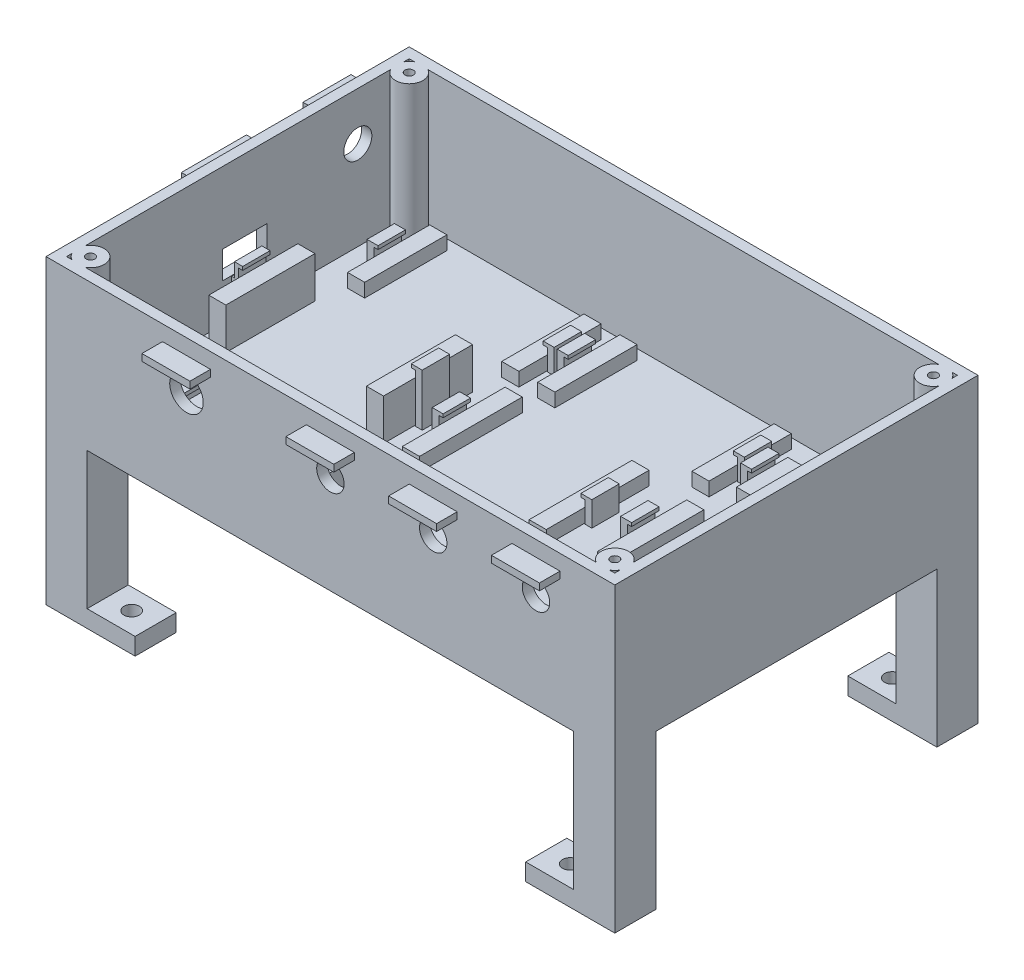
SolidWorks part; units mm, degrees
material "PETG"
ref_plane "Front Plane" through (0, 0, 0) normal (0, 0, 1) x (1, 0, 0)
ref_plane "Top Plane" through (0, 0, 0) normal (0, 1, 0) x (1, 0, 0)
ref_plane "Right Plane" through (0, 0, 0) normal (1, 0, 0) x (0, 0, -1)
other "Configuration Table"
sketch "Sketch1" plane through (0, 0, 0) normal (0, 1, 0) x (1, 0, 0)
  line L0 (-83, -53) -> (83, -53)
  line L1 (83, -53) -> (83, 53)
  line L2 (83, 53) -> (-83, 53)
  line L3 (-83, 53) -> (-83, -53)
extrude "Box_Shell" add sketch "Sketch1" along normal blind 43 from offset 45
sketch "Sketch2" plane through (0, 0, 0) normal (0, 1, 0) x (1, 0, 0)
  line L1 (-80, -50) -> (80, -50)
  line L2 (-80, -50) -> (-80, 50)
  line L3 (-80, 50) -> (80, 50)
  line L4 (80, -50) -> (80, 50)
  line L5 (-80, -50) -> (80, 50) construction
  line L6 (-80, 50) -> (80, -50) construction
  point P6 (0, 0)
  dimension "D1" = 160
  dimension "D2" = 100
extrude "Box_Cavity" cut sketch "Sketch2" against normal blind 40 from offset 88
sketch "Sketch3" plane through (0, 0, 0) normal (0, 1, 0) x (1, 0, 0)
  circle A0 centre (-76.5, 46.5) radius 4
  circle A1 centre (-76.5, -46.5) radius 4
  circle A2 centre (76.5, 46.5) radius 4
  circle A3 centre (76.5, -46.5) radius 4
  dimension "D1" = 8
  dimension "D2" = 8
  dimension "D3" = 8
  dimension "D4" = 8
extrude "Lid_Bosses" add sketch "Sketch3" along normal blind 40 from offset 48
sketch "Sketch4" plane through (0, 0, 0) normal (0, 1, 0) x (1, 0, 0)
  circle A0 centre (-76.5, 46.5) radius 1.25
  circle A1 centre (-76.5, -46.5) radius 1.25
  circle A2 centre (76.5, 46.5) radius 1.25
  circle A3 centre (76.5, -46.5) radius 1.25
  dimension "D1" = 2.5
  dimension "D2" = 2.5
  dimension "D3" = 2.5
  dimension "D4" = 2.5
extrude "Lid_Screw_Holes_M3" cut sketch "Sketch4" against normal blind 12 from offset 88
sketch "Sketch5" plane through (0, 0, 0) normal (0, 1, 0) x (1, 0, 0)
  line L0 (-83, 41) -> (-71, 41)
  line L1 (-71, 41) -> (-71, 53)
  line L2 (-71, 53) -> (-83, 53)
  line L3 (-83, 53) -> (-83, 41)
  line L4 (-83, -53) -> (-71, -53)
  line L5 (-71, -53) -> (-71, -41)
  line L6 (-71, -41) -> (-83, -41)
  line L7 (-83, -41) -> (-83, -53)
  line L8 (71, 41) -> (83, 41)
  line L9 (83, 41) -> (83, 53)
  line L10 (83, 53) -> (71, 53)
  line L11 (71, 53) -> (71, 41)
  line L12 (71, -53) -> (83, -53)
  line L13 (83, -53) -> (83, -41)
  line L14 (83, -41) -> (71, -41)
  line L15 (71, -41) -> (71, -53)
extrude "Legs" add sketch "Sketch5" along normal blind 45
sketch "Sketch6" plane through (0, 0, 0) normal (0, 1, 0) x (1, 0, 0)
  line L0 (-83, 41) -> (-57, 41)
  line L1 (-57, 41) -> (-57, 53)
  line L2 (-57, 53) -> (-83, 53)
  line L3 (-83, 53) -> (-83, 41)
  line L4 (-83, -53) -> (-57, -53)
  line L5 (-57, -53) -> (-57, -41)
  line L6 (-57, -41) -> (-83, -41)
  line L7 (-83, -41) -> (-83, -53)
  line L8 (57, 41) -> (83, 41)
  line L9 (83, 41) -> (83, 53)
  line L10 (83, 53) -> (57, 53)
  line L11 (57, 53) -> (57, 41)
  line L12 (57, -53) -> (83, -53)
  line L13 (83, -53) -> (83, -41)
  line L14 (83, -41) -> (57, -41)
  line L15 (57, -41) -> (57, -53)
extrude "Leg_Pads" add sketch "Sketch6" along normal blind 5
sketch "Sketch7" plane through (0, 0, 0) normal (0, 1, 0) x (1, 0, 0)
  circle A0 centre (-64, 47) radius 2.25
  circle A1 centre (-64, -47) radius 2.25
  circle A2 centre (64, 47) radius 2.25
  circle A3 centre (64, -47) radius 2.25
  dimension "D1" = 4.5
  dimension "D2" = 4.5
  dimension "D3" = 4.5
  dimension "D4" = 4.5
extrude "Leg_Holes_M4" cut sketch "Sketch7" along normal blind 6 from offset 0.5
sketch "Sketch8" plane through (0, 0, 0) normal (0, 1, 0) x (1, 0, 0)
  line L0 (-19, -13) -> (-14, -13)
  line L1 (-14, -13) -> (-14, 17)
  line L2 (-14, 17) -> (-19, 17)
  line L3 (-19, 17) -> (-19, -13)
  line L4 (18, -13) -> (23, -13)
  line L5 (23, -13) -> (23, 17)
  line L6 (23, 17) -> (18, 17)
  line L7 (18, 17) -> (18, -13)
  line L8 (36, -11) -> (41, -11)
  line L9 (41, -11) -> (41, 15)
  line L10 (41, 15) -> (36, 15)
  line L11 (36, 15) -> (36, -11)
  line L12 (69, -11) -> (74, -11)
  line L13 (74, -11) -> (74, 15)
  line L14 (74, 15) -> (69, 15)
  line L15 (69, 15) -> (69, -11)
  line L16 (-71, 23) -> (-66, 23)
  line L17 (-66, 23) -> (-66, 47)
  line L18 (-66, 47) -> (-71, 47)
  line L19 (-71, 47) -> (-71, 23)
  line L20 (-26, 23) -> (-21, 23)
  line L21 (-21, 23) -> (-21, 47)
  line L22 (-21, 47) -> (-26, 47)
  line L23 (-26, 47) -> (-26, 23)
  line L24 (-15.5, 23) -> (-10.5, 23)
  line L25 (-10.5, 23) -> (-10.5, 47)
  line L26 (-10.5, 47) -> (-15.5, 47)
  line L27 (-15.5, 47) -> (-15.5, 23)
  line L28 (29.5, 23) -> (34.5, 23)
  line L29 (34.5, 23) -> (34.5, 47)
  line L30 (34.5, 47) -> (29.5, 47)
  line L31 (29.5, 47) -> (29.5, 23)
  line L32 (40, 25.5) -> (45, 25.5)
  line L33 (45, 25.5) -> (45, 40.5)
  line L34 (45, 40.5) -> (40, 40.5)
  line L35 (40, 40.5) -> (40, 25.5)
  line L36 (69, 25.5) -> (74, 25.5)
  line L37 (74, 25.5) -> (74, 40.5)
  line L38 (74, 40.5) -> (69, 40.5)
  line L39 (69, 40.5) -> (69, 25.5)
  line L40 (-62, -46) -> (-57, -46)
  line L41 (-57, -46) -> (-57, -18)
  line L42 (-57, -18) -> (-62, -18)
  line L43 (-62, -18) -> (-62, -46)
  line L44 (-27, -46) -> (-22, -46)
  line L45 (-22, -46) -> (-22, -18)
  line L46 (-22, -18) -> (-27, -18)
  line L47 (-27, -18) -> (-27, -46)
extrude "Board_Pads_4mm" add sketch "Sketch8" along normal blind 4 from offset 48
sketch "Sketch9" plane through (0, 0, 0) normal (0, 1, 0) x (1, 0, 0)
  line L0 (-21.3, -2) -> (-19.3, -2)
  line L1 (-19.3, -2) -> (-19.3, 6)
  line L2 (-19.3, 6) -> (-21.3, 6)
  line L3 (-21.3, 6) -> (-21.3, -2)
  line L4 (23.3, -2) -> (25.3, -2)
  line L5 (25.3, -2) -> (25.3, 6)
  line L6 (25.3, 6) -> (23.3, 6)
  line L7 (23.3, 6) -> (23.3, -2)
  line L8 (33.7, -2) -> (35.7, -2)
  line L9 (35.7, -2) -> (35.7, 6)
  line L10 (35.7, 6) -> (33.7, 6)
  line L11 (33.7, 6) -> (33.7, -2)
  line L12 (74.3, -2) -> (76.3, -2)
  line L13 (76.3, -2) -> (76.3, 6)
  line L14 (76.3, 6) -> (74.3, 6)
  line L15 (74.3, 6) -> (74.3, -2)
  line L16 (-73.3, 31) -> (-71.3, 31)
  line L17 (-71.3, 31) -> (-71.3, 39)
  line L18 (-71.3, 39) -> (-73.3, 39)
  line L19 (-73.3, 39) -> (-73.3, 31)
  line L20 (-20.7, 31) -> (-18.7, 31)
  line L21 (-18.7, 31) -> (-18.7, 39)
  line L22 (-18.7, 39) -> (-20.7, 39)
  line L23 (-20.7, 39) -> (-20.7, 31)
  line L24 (-17.8, 31) -> (-15.8, 31)
  line L25 (-15.8, 31) -> (-15.8, 39)
  line L26 (-15.8, 39) -> (-17.8, 39)
  line L27 (-17.8, 39) -> (-17.8, 31)
  line L28 (34.8, 31) -> (36.8, 31)
  line L29 (36.8, 31) -> (36.8, 39)
  line L30 (36.8, 39) -> (34.8, 39)
  line L31 (34.8, 39) -> (34.8, 31)
  line L32 (37.7, 29) -> (39.7, 29)
  line L33 (39.7, 29) -> (39.7, 37)
  line L34 (39.7, 37) -> (37.7, 37)
  line L35 (37.7, 37) -> (37.7, 29)
  line L36 (74.3, 29) -> (76.3, 29)
  line L37 (76.3, 29) -> (76.3, 37)
  line L38 (76.3, 37) -> (74.3, 37)
  line L39 (74.3, 37) -> (74.3, 29)
  line L40 (-64.3, -36) -> (-62.3, -36)
  line L41 (-62.3, -36) -> (-62.3, -28)
  line L42 (-62.3, -28) -> (-64.3, -28)
  line L43 (-64.3, -28) -> (-64.3, -36)
  line L44 (-21.7, -36) -> (-19.7, -36)
  line L45 (-19.7, -36) -> (-19.7, -28)
  line L46 (-19.7, -28) -> (-21.7, -28)
  line L47 (-21.7, -28) -> (-21.7, -36)
extrude "Board_Clips_4mm" add sketch "Sketch9" along normal blind 7.2 from offset 48
sketch "Sketch10" plane through (0, 0, 0) normal (0, 1, 0) x (1, 0, 0)
  line L0 (-19.3, -2) -> (-18.1, -2)
  line L1 (-18.1, -2) -> (-18.1, 6)
  line L2 (-18.1, 6) -> (-19.3, 6)
  line L3 (-19.3, 6) -> (-19.3, -2)
  line L4 (22.1, -2) -> (23.3, -2)
  line L5 (23.3, -2) -> (23.3, 6)
  line L6 (23.3, 6) -> (22.1, 6)
  line L7 (22.1, 6) -> (22.1, -2)
  line L8 (35.7, -2) -> (36.9, -2)
  line L9 (36.9, -2) -> (36.9, 6)
  line L10 (36.9, 6) -> (35.7, 6)
  line L11 (35.7, 6) -> (35.7, -2)
  line L12 (73.1, -2) -> (74.3, -2)
  line L13 (74.3, -2) -> (74.3, 6)
  line L14 (74.3, 6) -> (73.1, 6)
  line L15 (73.1, 6) -> (73.1, -2)
  line L16 (-71.3, 31) -> (-70.1, 31)
  line L17 (-70.1, 31) -> (-70.1, 39)
  line L18 (-70.1, 39) -> (-71.3, 39)
  line L19 (-71.3, 39) -> (-71.3, 31)
  line L20 (-21.9, 31) -> (-20.7, 31)
  line L21 (-20.7, 31) -> (-20.7, 39)
  line L22 (-20.7, 39) -> (-21.9, 39)
  line L23 (-21.9, 39) -> (-21.9, 31)
  line L24 (-15.8, 31) -> (-14.6, 31)
  line L25 (-14.6, 31) -> (-14.6, 39)
  line L26 (-14.6, 39) -> (-15.8, 39)
  line L27 (-15.8, 39) -> (-15.8, 31)
  line L28 (33.6, 31) -> (34.8, 31)
  line L29 (34.8, 31) -> (34.8, 39)
  line L30 (34.8, 39) -> (33.6, 39)
  line L31 (33.6, 39) -> (33.6, 31)
  line L32 (39.7, 29) -> (40.9, 29)
  line L33 (40.9, 29) -> (40.9, 37)
  line L34 (40.9, 37) -> (39.7, 37)
  line L35 (39.7, 37) -> (39.7, 29)
  line L36 (73.1, 29) -> (74.3, 29)
  line L37 (74.3, 29) -> (74.3, 37)
  line L38 (74.3, 37) -> (73.1, 37)
  line L39 (73.1, 37) -> (73.1, 29)
  line L40 (-62.3, -36) -> (-61.1, -36)
  line L41 (-61.1, -36) -> (-61.1, -28)
  line L42 (-61.1, -28) -> (-62.3, -28)
  line L43 (-62.3, -28) -> (-62.3, -36)
  line L44 (-22.9, -36) -> (-21.7, -36)
  line L45 (-21.7, -36) -> (-21.7, -28)
  line L46 (-21.7, -28) -> (-22.9, -28)
  line L47 (-22.9, -28) -> (-22.9, -36)
extrude "Clip_Lips_4mm" add sketch "Sketch10" along normal blind 1 from offset 54.2
sketch "Sketch11" plane through (0, 0, 0) normal (0, 1, 0) x (1, 0, 0)
  line L0 (-77.5, -11) -> (-72.5, -11)
  line L1 (-72.5, -11) -> (-72.5, 15)
  line L2 (-72.5, 15) -> (-77.5, 15)
  line L3 (-77.5, 15) -> (-77.5, -11)
  line L4 (-31.5, -11) -> (-26.5, -11)
  line L5 (-26.5, -11) -> (-26.5, 15)
  line L6 (-26.5, 15) -> (-31.5, 15)
  line L7 (-31.5, 15) -> (-31.5, -11)
extrude "Board_Pads_12mm" add sketch "Sketch11" along normal blind 12 from offset 48
sketch "Sketch12" plane through (0, 0, 0) normal (0, 1, 0) x (1, 0, 0)
  line L0 (-79.8, -2) -> (-77.8, -2)
  line L1 (-77.8, -2) -> (-77.8, 6)
  line L2 (-77.8, 6) -> (-79.8, 6)
  line L3 (-79.8, 6) -> (-79.8, -2)
  line L4 (-26.2, -2) -> (-24.2, -2)
  line L5 (-24.2, -2) -> (-24.2, 6)
  line L6 (-24.2, 6) -> (-26.2, 6)
  line L7 (-26.2, 6) -> (-26.2, -2)
extrude "Board_Clips_12mm" add sketch "Sketch12" along normal blind 15.2 from offset 48
sketch "Sketch13" plane through (0, 0, 0) normal (0, 1, 0) x (1, 0, 0)
  line L0 (-77.8, -2) -> (-76.6, -2)
  line L1 (-76.6, -2) -> (-76.6, 6)
  line L2 (-76.6, 6) -> (-77.8, 6)
  line L3 (-77.8, 6) -> (-77.8, -2)
  line L4 (-27.4, -2) -> (-26.2, -2)
  line L5 (-26.2, -2) -> (-26.2, 6)
  line L6 (-26.2, 6) -> (-27.4, 6)
  line L7 (-27.4, 6) -> (-27.4, -2)
extrude "Clip_Lips_12mm" add sketch "Sketch13" along normal blind 1 from offset 62.2
sketch "Sketch14" plane through (0, 0, 0) normal (0, 0, 1) x (1, 0, 0)
  circle A0 centre (-42, 74) radius 4.9
  circle A1 centre (0, 74) radius 4
  circle A2 centre (30, 74) radius 4
  circle A3 centre (60, 74) radius 4
  dimension "D1" = 9.8
  dimension "D2" = 8
  dimension "D3" = 8
  dimension "D4" = 8
extrude "Front_Wall_Holes" cut sketch "Sketch14" along normal blind 5 from offset 49
sketch "Sketch15" plane through (0, 0, 0) normal (0, 1, 0) x (1, 0, 0)
  line L0 (-49, -59) -> (-35, -59)
  line L1 (-35, -59) -> (-35, -53)
  line L2 (-35, -53) -> (-49, -53)
  line L3 (-49, -53) -> (-49, -59)
  line L4 (-7, -59) -> (7, -59)
  line L5 (7, -59) -> (7, -53)
  line L6 (7, -53) -> (-7, -53)
  line L7 (-7, -53) -> (-7, -59)
  line L8 (23, -59) -> (37, -59)
  line L9 (37, -59) -> (37, -53)
  line L10 (37, -53) -> (23, -53)
  line L11 (23, -53) -> (23, -59)
  line L12 (53, -59) -> (67, -59)
  line L13 (67, -59) -> (67, -53)
  line L14 (67, -53) -> (53, -53)
  line L15 (53, -53) -> (53, -59)
extrude "Front_Drip_Lips" add sketch "Sketch15" along normal blind 2 from offset 81.5
sketch "Sketch16" plane through (0, 0, 0) normal (1, 0, 0) x (0, 0, -1)
  line L1 (-4.5, 59.1) -> (8.5, 59.1)
  line L2 (-4.5, 59.1) -> (-4.5, 67.1)
  line L3 (-4.5, 67.1) -> (8.5, 67.1)
  line L4 (8.5, 59.1) -> (8.5, 67.1)
  line L5 (-4.5, 59.1) -> (8.5, 67.1) construction
  line L6 (-4.5, 67.1) -> (8.5, 59.1) construction
  circle A0 centre (35, 74) radius 4.1
  point P2 (2, 63.1)
  point P7 (2, 63.1)
  dimension "D1" = 8.2
  dimension "D2" = 13
  dimension "D3" = 8
extrude "Left_Wall_Holes" cut sketch "Sketch16" along normal blind 5 from offset 84
sketch "Sketch17" plane through (0, 0, 0) normal (0, 1, 0) x (1, 0, 0)
  line L0 (-89, 28) -> (-83, 28)
  line L1 (-83, 28) -> (-83, 42)
  line L2 (-83, 42) -> (-89, 42)
  line L3 (-89, 42) -> (-89, 28)
  line L4 (-89, -7.5) -> (-83, -7.5)
  line L5 (-83, -7.5) -> (-83, 11.5)
  line L6 (-83, 11.5) -> (-89, 11.5)
  line L7 (-89, 11.5) -> (-89, -7.5)
extrude "Left_Drip_Lips" add sketch "Sketch17" along normal blind 2 from offset 81.5
equation "\"Jar_OD\"= 90  'ASSUMED - Part C fallback - jar outer diameter"
equation "\"Jar_H\"= 120  'ASSUMED - Part C fallback - jar height"
equation "\"Pump_L\"= 45  'ASSUMED - Part C fallback"
equation "\"Pump_W\"= 24  'ASSUMED - Part C fallback"
equation "\"Pump_H\"= 33  'ASSUMED - Part C fallback"
equation "\"Pump_Outlet_OD\"= 7.5  'ASSUMED - Part C fallback"
equation "\"Tube_OD\"= 8  'ASSUMED - Part C fallback"
equation "\"Tube_ID\"= 6  'ASSUMED - Part C fallback"
equation "\"TDS_Body_Dia\"= 12  'ASSUMED - Part C fallback"
equation "\"TDS_Wet_Len\"= 45  'ASSUMED - Part C fallback - length in water"
equation "\"DS_Tube_Dia\"= 6  'ASSUMED - Part C fallback"
equation "\"DS_Tube_Len\"= 50  'ASSUMED - Part C fallback"
equation "\"ORP_Body_Dia\"= 12  'ASSUMED - Part C fallback"
equation "\"ORP_Body_Len\"= 150  'ASSUMED - Part C fallback"
equation "\"ORP_Cap_Dia\"= 16  'ASSUMED - Part C fallback"
equation "\"Turb_W\"= 33  'ASSUMED - Part C fallback - head width"
equation "\"Turb_D\"= 28  'ASSUMED - Part C fallback - head depth"
equation "\"Turb_H\"= 30  'ASSUMED - Part C fallback - head height"
equation "\"Turb_Slot_W\"= 10  'ASSUMED - Part C fallback - slot width"
equation "\"Flow_L\"= 62  'ASSUMED - Part C fallback YF-S201"
equation "\"Flow_W\"= 36  'ASSUMED - Part C fallback"
equation "\"Flow_H\"= 35  'ASSUMED - Part C fallback"
equation "\"Thread_G12_OD\"= 20.955  'ASSUMED - Part C fallback thread G1/2 (major diameter)"
equation "\"Valve_L\"= 75  'ASSUMED - Part C fallback"
equation "\"Valve_W\"= 45  'ASSUMED - Part C fallback"
equation "\"Valve_H\"= 60  'ASSUMED - Part C fallback"
equation "\"Tee_L\"= 40  'ASSUMED - Part C fallback - overall length"
equation "\"Tee_Branch_L\"= 25  'ASSUMED - Part C fallback"
equation "\"Tee_OD\"= 12  'ASSUMED - Part C fallback"
equation "\"Cuv_W\"= 12.5  'ASSUMED - Part C fallback"
equation "\"Cuv_D\"= 12.5  'ASSUMED - Part C fallback"
equation "\"Cuv_H\"= 45  'ASSUMED - Part C fallback"
equation "\"LED_Board_L\"= 20  'ASSUMED - Part C fallback"
equation "\"LED_Board_W\"= 20  'ASSUMED - Part C fallback - LED at centre"
equation "\"GUVA_L\"= 20  'ASSUMED - Part C fallback"
equation "\"GUVA_W\"= 12  'ASSUMED - Part C fallback - sensor at centre"
equation "\"Reed_L\"= 27  'ASSUMED - Part C fallback MC-38 half"
equation "\"Reed_W\"= 14  'ASSUMED - Part C fallback"
equation "\"Reed_H\"= 8  'ASSUMED - Part C fallback"
equation "\"ESP_L\"= 51  'ASSUMED - Part C fallback"
equation "\"ESP_W\"= 28  'ASSUMED - Part C fallback"
equation "\"TFT_L\"= 58  'ASSUMED - Part C fallback - board"
equation "\"TFT_W\"= 35  'ASSUMED - Part C fallback - board"
equation "\"TFT_Win_L\"= 35  'ASSUMED - Part C fallback - visible window"
equation "\"TFT_Win_W\"= 28  'ASSUMED - Part C fallback - visible window"
equation "\"Relay_L\"= 50  'ASSUMED - Part C fallback"
equation "\"Relay_W\"= 26  'ASSUMED - Part C fallback"
equation "\"Relay_H\"= 19  'ASSUMED - Part C fallback"
equation "\"Mosfet_L\"= 34  'ASSUMED - Part C fallback"
equation "\"Mosfet_W\"= 17  'ASSUMED - Part C fallback"
equation "\"Mosfet_H\"= 12  'ASSUMED - Part C fallback"
equation "\"TDS_Board_L\"= 42  'ASSUMED - Part C fallback"
equation "\"TDS_Board_W\"= 32  'ASSUMED - Part C fallback"
equation "\"Turb_Board_L\"= 38  'ASSUMED - Part C fallback"
equation "\"Turb_Board_W\"= 28  'ASSUMED - Part C fallback"
equation "\"BNC_Thread_Dia\"= 9.5  'ASSUMED - Part C fallback"
equation "\"Plate_L\"= 420  'ASSUMED - Part C fallback"
equation "\"Plate_W\"= 297  'ASSUMED - Part C fallback"
equation "\"Plate_T\"= 6  'ASSUMED - Part C fallback"
equation "\"Probe_Clr\"= 0.3  'DESIGN VALUE - Part C rule 3 - printed probe hole = diameter + 0.3"
equation "\"Cuv_Clr\"= 0.2  'DESIGN VALUE - Part C rule 3 - cuvette pocket = size + 0.2"
equation "\"Label_H\"= 0.6  'DESIGN VALUE - Part D - raised label height"
equation "\"D1@Sketch2\" = 160.0"
equation "\"D2@Sketch2\" = 100.0"
equation "\"D1@Box_Cavity\" = 40.0"
equation "\"D2@Sketch16\" = 13.0"
equation "\"D3@Sketch16\" = 8.0"
